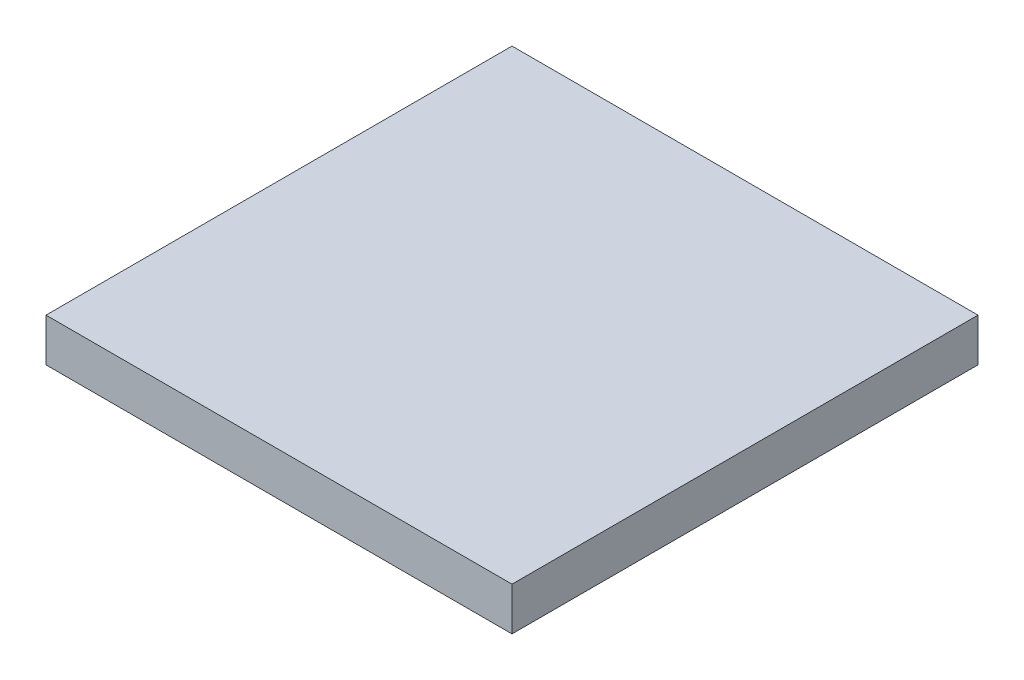
SolidWorks part; units mm, degrees
ref_plane "Front Plane" through (0, 0, 0) normal (0, 0, 1) x (1, 0, 0)
ref_plane "Top Plane" through (0, 0, 0) normal (0, 1, 0) x (1, 0, 0)
ref_plane "Right Plane" through (0, 0, 0) normal (1, 0, 0) x (0, 0, -1)
sketch "Sketch1" plane through (0, 0, 0) normal (0, 1, 0) x (1, 0, 0)
  line L1 (-274.6375, 274.6375) -> (274.6375, 274.6375)
  line L2 (-274.6375, 274.6375) -> (-274.6375, -274.6375)
  line L3 (-274.6375, -274.6375) -> (274.6375, -274.6375)
  line L4 (274.6375, 274.6375) -> (274.6375, -274.6375)
  line L5 (-274.6375, 274.6375) -> (274.6375, -274.6375) construction
  line L6 (-274.6375, -274.6375) -> (274.6375, 274.6375) construction
  point P0 (0, 0)
  dimension "Length" = 549.275
  dimension "Width" = 549.275
extrude "Boss-Extrude1" add sketch "Sketch1" along normal blind 50.8
